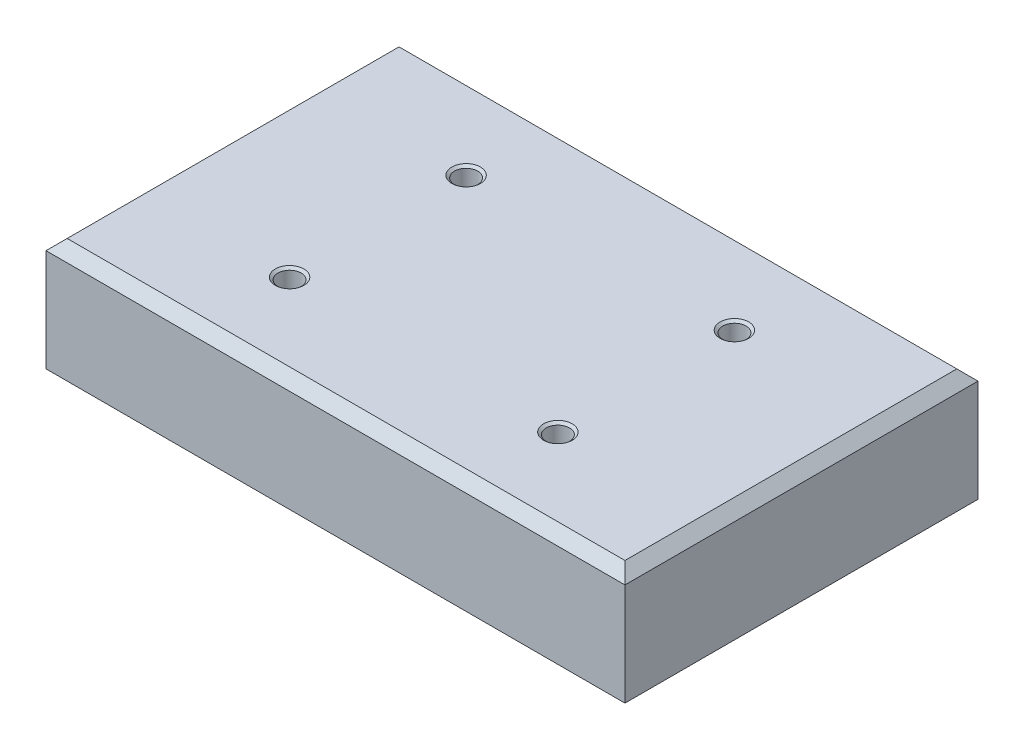
SolidWorks part; units mm, degrees
ref_plane "Front Plane" through (0, 0, 0) normal (0, 0, 1) x (1, 0, 0)
ref_plane "Top Plane" through (0, 0, 0) normal (0, 1, 0) x (1, 0, 0)
ref_plane "Right Plane" through (0, 0, 0) normal (1, 0, 0) x (0, 0, -1)
sketch "Sketch1" plane through (0, 0, 0) normal (0, 1, 0) x (1, 0, 0)
  line L1 (-41, 25) -> (41, 25)
  line L2 (-41, 25) -> (-41, -25)
  line L3 (-41, -25) -> (41, -25)
  line L4 (41, 25) -> (41, -25)
  point P0 (0, 0)
  dimension "D1" = 82
  dimension "D2" = 41
  dimension "D3" = 50
  dimension "D4" = 25
extrude "Boss-Extrude1" add sketch "Sketch1" along normal blind 16
chamfer "Chamfer1" distance 1.5 angle 45 1 edges at (-41, 16, 0)
chamfer "Chamfer2" distance 1.5 angle 45 1 edges at (0.75, 16, 25)
chamfer "Chamfer3" distance 1.5 angle 45 1 edges at (41, 16, -0.75)
chamfer "Chamfer4" distance 1.5 angle 45 1 edges at (0, 16, -25)
hole_wizard "M4 Tapped Hole4" positions "Sketch9" profile "Sketch10" tap size "M4" standard "DIN"
sketch "Sketch9" plane through (0, 16, 0) normal (0, 1, 0) x (1, 0, 0)
  line L0 (0, 25) -> (0, 0) construction
  line L1 (-41, 25) -> (41, 25) construction
  line L2 (0, 0) -> (-41, 0) construction
  line L3 (-41, -25) -> (-41, 25) construction
  point P0 (-19, 12.5)
  point P2 (19, 12.5)
  point P4 (19, -12.5)
  point P6 (-19, -12.5)
  dimension "D1" = 38
  dimension "D2" = 25
sketch "Sketch10" plane through (-19, 16, -12.5) normal (1, 0, 0) x (0, 0, 1)
  line L0 (0, 0) -> (0, 8.9914)
  line L1 (0, 8.9914) -> (1.65, 8)
  line L2 (1.65, 8) -> (1.65, 0.3147)
  line L3 (1.65, 0.3147) -> (2.025, 0)
  line L5 (2.025, 0) -> (0, 0)
  line L6 (-1.65, 0.3147) -> (-2.025, 0) construction
  line L10 (0, 8.9914) -> (-1.65, 8) construction
  line L11 (0, -6.35) -> (0, 107.95) construction
  dimension "Tap Drill Dia." = 3.3
  dimension "Tap Drill Depth" = 8
  dimension "Near C'Sink Dia." = 4.05
  dimension "Near C'Sink Angle" = 100
  dimension "Drill Angle" = 118
cosmetic thread "Hole Thread13" parameters "D1"=6, "D2"=4
cosmetic thread "Hole Thread14" parameters "D1"=6, "D2"=4
cosmetic thread "Hole Thread15" parameters "D1"=6, "D2"=4
cosmetic thread "Hole Thread16" parameters "D1"=6, "D2"=4
